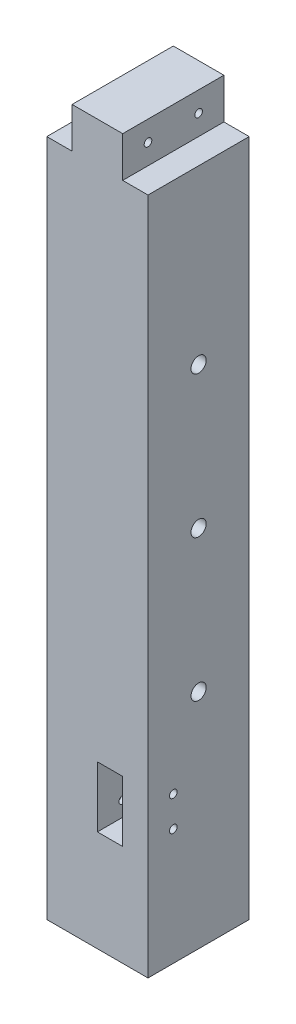
SolidWorks part; units mm, degrees
material "Pine"
ref_plane "Front Plane" through (0, 0, 0) normal (0, 0, 1) x (1, 0, 0)
ref_plane "Top Plane" through (0, 0, 0) normal (0, 1, 0) x (1, 0, 0)
ref_plane "Right Plane" through (0, 0, 0) normal (1, 0, 0) x (0, 0, -1)
sketch "Sketch1" plane through (0, 0, 0) normal (0, 0, 1) x (1, 0, 0)
  line L1 (63.5, 425.45) -> (-63.5, 425.45)
  line L2 (63.5, 425.45) -> (63.5, -425.45)
  line L3 (63.5, -425.45) -> (-63.5, -425.45)
  line L4 (-63.5, 425.45) -> (-63.5, -425.45)
  line L5 (63.5, 425.45) -> (-63.5, -425.45) construction
  line L6 (63.5, -425.45) -> (-63.5, 425.45) construction
  line L7 (31.75, 476.25) -> (-31.75, 476.25)
  line L8 (31.75, 476.25) -> (31.75, 374.65)
  line L9 (31.75, 374.65) -> (-31.75, 374.65)
  line L10 (-31.75, 476.25) -> (-31.75, 374.65)
  line L11 (31.75, 476.25) -> (-31.75, 374.65) construction
  line L12 (31.75, 374.65) -> (-31.75, 476.25) construction
  point P0 (0, 0)
  point P6 (0, 425.45)
  dimension "D1" = 101.6
  dimension "D2" = 901.7
  dimension "D3" = 127
  dimension "D4" = 63.5
extrude "Boss-Extrude1" add sketch "Sketch1" along normal blind 127 contours L10 L1 L4 L3 L2 L8 L9 | L1 L10 L9 L8 | L7 L10 L1 L8
sketch "Sketch2" plane through (0, 0, 127) normal (0, 0, 1) x (1, 0, 0)
  line L0 (63.5, 425.45) -> (63.5, -425.45) construction
  line L1 (31.75, -222.25) -> (0, -222.25)
  line L2 (31.75, -222.25) -> (31.75, -298.45)
  line L3 (31.75, -298.45) -> (0, -298.45)
  line L4 (0, -222.25) -> (0, -298.45)
  line L5 (31.75, -222.25) -> (0, -298.45) construction
  line L6 (31.75, -298.45) -> (0, -222.25) construction
  line L7 (63.5, -425.45) -> (-63.5, -425.45) construction
  point P0 (15.875, -260.35)
  dimension "D1" = 31.75
  dimension "D2" = 76.2
  dimension "D3" = 31.75
  dimension "D4" = 127
extrude "Cut-Extrude1" cut sketch "Sketch2" against normal blind 63.5
sketch "Sketch3" plane through (-63.5, 0, 0) normal (-1, 0, 0) x (0, 0, 1)
  line L0 (0, 425.45) -> (0, -425.45) construction
  line L1 (63.5, -222.25) -> (31.75, -222.25)
  line L2 (63.5, -222.25) -> (63.5, -298.45)
  line L3 (63.5, -298.45) -> (31.75, -298.45)
  line L4 (31.75, -222.25) -> (31.75, -298.45)
  line L5 (63.5, -222.25) -> (31.75, -298.45) construction
  line L6 (63.5, -298.45) -> (31.75, -222.25) construction
  line L7 (127, -425.45) -> (0, -425.45) construction
  point P0 (47.625, -260.35)
  dimension "D1" = 76.2
  dimension "D2" = 31.75
  dimension "D3" = 127
  dimension "D4" = 31.75
extrude "Cut-Extrude3" cut sketch "Sketch3" against normal blind 63.246
sketch "Sketch4" plane through (-63.5, 0, 0) normal (-1, 0, 0) x (0, 0, 1)
  line L0 (63.5, 381) -> (63.5, -49619) construction
  line L1 (127, 425.45) -> (0, 425.45) construction
  line L2 (127, -425.45) -> (0, -425.45) construction
  circle A0 centre (63.5, -146.05) radius 9.525
  circle A1 centre (63.5, 31.75) radius 9.525
  circle A2 centre (63.5, 209.55) radius 9.525
  point P4 (63.5, 425.45)
  dimension "D1" = 19.05
  dimension "D2" = 177.8
  dimension "D3" = 177.8
  dimension "D4" = 279.4
extrude "Cut-Extrude4" cut sketch "Sketch4" against normal through all
sketch "Sketch5" plane through (0, 0, 0) normal (0, 0, -1) x (-1, 0, 0)
  line L0 (31.75, -222.25) -> (31.75, -298.45) construction
  line L4 (63.5, -298.45) -> (63.5, -222.25)
  line L5 (0.254, -298.45) -> (63.5, -298.45)
  line L6 (0.254, -222.25) -> (0.254, -298.45)
  line L7 (63.5, -222.25) -> (0.254, -222.25)
  line L8 (63.5, -298.45) -> (63.5, -222.25)
  line L9 (0.254, -298.45) -> (63.5, -298.45)
  line L10 (0.254, -222.25) -> (0.254, -298.45)
  line L11 (63.5, -222.25) -> (0.254, -222.25)
  circle A0 centre (31.75, -279.4) radius 4.7625
  circle A1 centre (31.75, -241.3) radius 4.7625
  point P10 (31.75, -260.35)
  dimension "D4" = 9.525
  dimension "D2" = 19.05
  dimension "D3" = 19.05
  dimension "D5" = 31.75
  dimension "D1" = 0
extrude "Cut-Extrude5" cut sketch "Sketch5" against normal blind 69.85 contours A0 L0 | L0 A0 | A1 L0 | L0 A1
sketch "Sketch6" plane through (63.5, 0, 0) normal (1, 0, 0) x (0, 0, -1)
  line L0 (-95.25, -222.25) -> (-95.25, -298.45) construction
  line L4 (-127, -222.25) -> (-127, -298.45)
  line L5 (-63.5, -222.25) -> (-127, -222.25)
  line L6 (-63.5, -298.45) -> (-63.5, -222.25)
  line L7 (-127, -298.45) -> (-63.5, -298.45)
  line L8 (-127, -222.25) -> (-127, -298.45)
  line L9 (-63.5, -222.25) -> (-127, -222.25)
  line L10 (-63.5, -298.45) -> (-63.5, -222.25)
  line L11 (-127, -298.45) -> (-63.5, -298.45)
  circle A0 centre (-95.25, -279.4) radius 4.7625
  circle A1 centre (-95.25, -241.3) radius 4.7625
  point P10 (-95.25, -260.35)
  dimension "D3" = 19.05
  dimension "D4" = 9.525
  dimension "D2" = 19.05
  dimension "D5" = 31.75
  dimension "D1" = 0
extrude "Cut-Extrude6" cut sketch "Sketch6" against normal blind 69.85 contours A1 L0 | L0 A1 | A0 L0 | L0 A0
sketch "Sketch7" plane through (31.75, 0, 0) normal (1, 0, 0) x (0, 0, -1)
  line L0 (-127, 450.85) -> (0, 450.85) construction
  line L1 (-127, 476.25) -> (-127, 425.45) construction
  line L2 (0, 476.25) -> (0, 425.45) construction
  circle A0 centre (-95.25, 450.85) radius 4.7625
  circle A1 centre (-31.75, 450.85) radius 4.7625
  point P10 (-63.5, 450.85)
  dimension "D1" = 31.75
  dimension "D3" = 9.525
  dimension "D2" = 31.75
extrude "Cut-Extrude7" cut sketch "Sketch7" against normal through all
